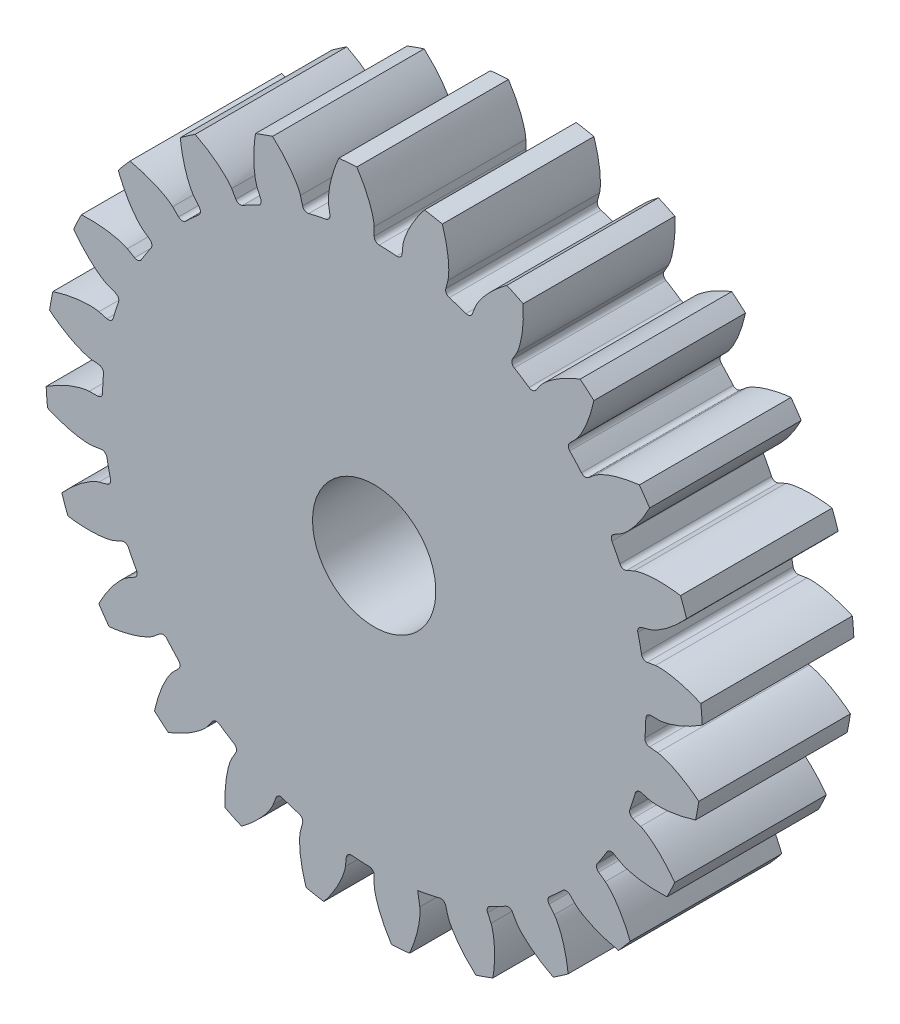
SolidWorks part; units mm, degrees
material "Brass"
ref_plane "Front Plane" through (0, 0, 0) normal (0, 0, 1) x (1, 0, 0)
ref_plane "Top Plane" through (0, 0, 0) normal (0, 1, 0) x (1, 0, 0)
ref_plane "Right Plane" through (0, 0, 0) normal (1, 0, 0) x (0, 0, -1)
sketch "Sketch3" plane through (0, 0, 0) normal (0, 0, 1) x (1, 0, 0)
  circle A0 centre (0, 0) radius 6.5
  dimension "D1" = 13
extrude "Boss-Extrude1" add sketch "Sketch3" along normal blind 3 contours A0
sketch "Sketch4" plane through (0, 0, 0) normal (0, 0, 1) x (1, 0, 0)
  line L0 (5.375, 0) -> (5.6382, 0)
  line L1 (0, 0) -> (6.4917, -0.3284) construction
  line L2 (5.3476, -0.5424) -> (5.6094, -0.569)
  circle A0 centre (0, 0) radius 6 construction
  circle A1 centre (0, 0) radius 5.6382 construction
  arc A2 (5.3476, -0.5424) -> (5.375, 0) centre (0, 0) ccw
  circle A3 centre (0, 0) radius 6.5 construction
  spline S0 degree 4 poles (5.6382, 0) (5.6436, 0.0001) (5.6538, 0.0007) (5.6704, 0.0021) (5.7032, 0.0063) (5.7401, 0.0126) (5.7816, 0.0215) (5.8259, 0.0327) (5.8637, 0.0433) (5.9012, 0.0548) (5.9385, 0.0672) (5.9834, 0.0831) (6.0369, 0.1037) (6.099, 0.1298) (6.1689, 0.1617) (6.2395, 0.1968) (6.3084, 0.2334) (6.3772, 0.2727) (6.4433, 0.3125) (6.5112, 0.3562) (6.5735, 0.3977) (6.6423, 0.4468) (6.6975, 0.4873) (6.7693, 0.5433) (6.8114, 0.5772) (6.8602, 0.6179) (6.8817, 0.6364) (6.895, 0.6478) knots 0 0 0 0 0 0.015084 0.028532 0.04661 0.092111 0.119476 0.146842 0.174209 0.201575 0.228941 0.256307 0.307035 0.361767 0.4165 0.471232 0.525964 0.580697 0.635429 0.690161 0.744894 0.799626 0.854358 0.909091 0.954545 1 1 1 1 1 construction
  spline S1 degree 4 poles (5.6382, 0) (5.6436, 0.0001) (5.6538, 0.0007) (5.6704, 0.0021) (5.7032, 0.0063) (5.7401, 0.0126) (5.7816, 0.0215) (5.8259, 0.0327) (5.8637, 0.0433) (5.9012, 0.0548) (5.9385, 0.0672) (5.9834, 0.0831) (6.0369, 0.1037) (6.099, 0.1298) (6.1689, 0.1617) (6.2395, 0.1968) (6.3084, 0.2334) (6.3772, 0.2727) (6.4433, 0.3125) (6.5112, 0.3562) (6.5735, 0.3977) (6.6423, 0.4468) (6.6975, 0.4873) (6.7537, 0.5312) (6.781, 0.5528) (6.7948, 0.5641) knots 0 0 0 0 0 0.015084 0.028532 0.04661 0.092111 0.119476 0.146842 0.174209 0.201575 0.228941 0.256307 0.307035 0.361767 0.4165 0.471232 0.525964 0.580697 0.635429 0.690161 0.744894 0.799626 0.854358 0.909091 0.909091 0.909091 0.909091 0.909091
  spline S2 degree 4 poles (106.284, -15.4902) (106.3203, -15.496) (106.4217, -15.5139) (106.6124, -15.5542) (106.9218, -15.6289) (107.4928, -15.787) (108.3484, -16.0665) (109.2774, -16.4238) (110.2481, -16.846) (111.0925, -17.2464) (111.7606, -17.5817) (112.5627, -18.0056) (113.5166, -18.5412) (114.6147, -19.2012) (115.8472, -19.9983) (117.0769, -20.8493) (118.2809, -21.7356) (119.4604, -22.6553) (120.4702, -23.4858) (121.322, -24.2171) (122.1596, -24.9594) (122.8519, -25.5935) (123.5262, -26.2293) (124.2037, -26.8891) (124.7206, -27.4019) (125.2693, -27.9609) (125.7445, -28.4521) (126.1894, -28.925) (126.4234, -29.1763) (126.5387, -29.301) knots 0 0 0 0 0 0.005377 0.015084 0.028532 0.04661 0.092111 0.146842 0.174209 0.201575 0.228941 0.256307 0.307035 0.361767 0.4165 0.471232 0.525964 0.580697 0.635429 0.662795 0.690161 0.744894 0.77226 0.799626 0.826992 0.854358 0.881725 0.909091 0.909091 0.909091 0.909091 0.909091
  spline S3 degree 4 poles (5.6094, -0.569) (5.6147, -0.5696) (5.6248, -0.5712) (5.6413, -0.5744) (5.6734, -0.5818) (5.7095, -0.5919) (5.7499, -0.6049) (5.7929, -0.6205) (5.8294, -0.6348) (5.8656, -0.6501) (5.9014, -0.6661) (5.9444, -0.6866) (5.9956, -0.7124) (6.0548, -0.7446) (6.1211, -0.7834) (6.1878, -0.8255) (6.2526, -0.8688) (6.3171, -0.9149) (6.3789, -0.9612) (6.442, -1.0115) (6.4998, -1.0591) (6.5632, -1.1149) (6.6141, -1.1607) (6.6656, -1.21) (6.6906, -1.2344) (6.7032, -1.2469) knots 0 0 0 0 0 0.015084 0.028532 0.04661 0.092111 0.119476 0.146842 0.174209 0.201575 0.228941 0.256307 0.307035 0.361767 0.4165 0.471232 0.525964 0.580697 0.635429 0.690161 0.744894 0.799626 0.854358 0.909091 0.909091 0.909091 0.909091 0.909091
  dimension "D1" = 12
  dimension "D2" = 11.2763
  dimension "D3" = 10.75
  dimension "D4" = 2.896
sketch "Sketch5" plane through (0, 0, 0) normal (0, 0, -1) x (-1, 0, 0)
sketch "Sketch6" plane through (0, 0, 3) normal (0, 0, 1) x (1, 0, 0)
  spline S0 degree 4 poles (5.584, -0.5665) (5.585, -0.5665) (5.5873, -0.5664) (5.5951, -0.5671) (5.607, -0.5685) (5.6218, -0.571) (5.6516, -0.5769) (5.6822, -0.5849) (5.7252, -0.5972) (5.7693, -0.6124) (5.8191, -0.6312) (5.8672, -0.6515) (5.9207, -0.6758) (5.9849, -0.7075) (6.0596, -0.7478) (6.144, -0.7981) (6.2321, -0.8553) (6.3184, -0.9165) (6.4018, -0.9797) (6.4843, -1.0471) (6.5626, -1.1145) (6.6423, -1.1885) (6.7141, -1.2577) (6.7935, -1.3404) (6.8551, -1.406) (6.9366, -1.4999) (6.9806, -1.5525) (7.0336, -1.6182) (7.0565, -1.6477) (7.07, -1.6651) knots 0 0 0 0 0 0.002436 0.00621 0.013651 0.025362 0.041878 0.0605 0.087814 0.115747 0.143681 0.171614 0.199547 0.239932 0.295799 0.351666 0.407532 0.463399 0.519266 0.575132 0.630999 0.686865 0.742732 0.798599 0.854465 0.910332 0.955166 1 1 1 1 1 construction
  spline S1 degree 4 poles (5.6094, -0.569) (5.6143, -0.5697) (5.6258, -0.5718) (5.6516, -0.5769) (5.6822, -0.5849) (5.7252, -0.5972) (5.7693, -0.6124) (5.8191, -0.6312) (5.8672, -0.6515) (5.9207, -0.6758) (5.9849, -0.7075) (6.0596, -0.7478) (6.144, -0.7981) (6.2321, -0.8553) (6.3184, -0.9165) (6.4018, -0.9797) (6.4843, -1.0471) (6.5626, -1.1145) (6.6423, -1.1885) (6.7141, -1.2577) (6.7935, -1.3404) (6.8551, -1.406) (6.9194, -1.4801) (6.9491, -1.5151) (6.9642, -1.5332) knots 0.013651 0.013651 0.013651 0.013651 0.013651 0.025362 0.041878 0.0605 0.087814 0.115747 0.143681 0.171614 0.199547 0.239932 0.295799 0.351666 0.407532 0.463399 0.519266 0.575132 0.630999 0.686865 0.742732 0.798599 0.854465 0.910332 0.910332 0.910332 0.910332 0.910332
sketch "Sketch7" plane through (0, 0, 0) normal (0, 0, -1) x (-1, 0, 0)
extrude "Cut-Extrude1" cut sketch "Sketch4" against normal through all and the other way through all contours S3 L2 A2 L0 S1
pattern_circular "CirPattern1" count 24 over 360 about axis through (0, 0, 0) along (0, 0, 1) of "Cut-Extrude1"
fillet "Fillet1" radius 0.1 48 edges at (5.3057, 0.8601, 1.5) (5.1919, 1.3912, 1.5) (4.9023, 2.204, 1.5) (4.6549, 2.6875, 1.5) (4.1649, 3.3977, 1.5) (3.8007, 3.8007, 1.5) (3.1435, 4.3599, 1.5) (2.6875, 4.6549, 1.5) (1.908, 5.025, 1.5) (1.3912, 5.1919, 1.5) (0.5424, 5.3476, 1.5) (0, 5.375, 1.5) (-0.8601, 5.3057, 1.5) (-1.3912, 5.1919, 1.5) (-2.204, 4.9023, 1.5) (-2.6875, 4.6549, 1.5) (-3.3977, 4.1649, 1.5) (-3.8007, 3.8007, 1.5) (-4.3599, 3.1435, 1.5) (-4.6549, 2.6875, 1.5) (-5.025, 1.908, 1.5) (-5.1919, 1.3912, 1.5) (-5.3476, 0.5424, 1.5) (-5.375, 0, 1.5) (-5.3057, -0.8601, 1.5) (-5.1919, -1.3912, 1.5) (-4.9023, -2.204, 1.5) (-4.6549, -2.6875, 1.5) (-4.1649, -3.3977, 1.5) (-3.8007, -3.8007, 1.5) (-3.1435, -4.3599, 1.5) (-2.6875, -4.6549, 1.5) (-1.908, -5.025, 1.5) (-1.3912, -5.1919, 1.5) (-0.5424, -5.3476, 1.5) (0, -5.375, 1.5) (0.9022, -5.5655, 1.5) (1.3912, -5.1919, 1.5) (2.6875, -4.6549, 1.5) (2.204, -4.9023, 1.5) (3.3977, -4.1649, 1.5) (3.8007, -3.8007, 1.5) (4.3599, -3.1435, 1.5) (4.6549, -2.6875, 1.5) (5.1919, -1.3912, 1.5) (5.025, -1.908, 1.5) (5.3476, -0.5424, 1.5) (5.375, 0, 1.5)
sketch "Sketch8" plane through (0, 0, 0) normal (0, 0, -1) x (-1, 0, 0)
  circle A0 centre (0, 0) radius 1.22
extrude "Cut-Extrude2" cut sketch "Sketch8" against normal through all
sketch "Sketch9" plane through (0, 0, 0) normal (0, 0, -1) x (-1, 0, 0)
  circle A0 centre (0, 0) radius 6
equation "\"P\"= 2'Diametral Pitch"
equation "\"N\"= 24'Numver of teeth"
equation "\"phi\"= 20deg'Pressure Angle"
equation "\"a\"= 1 / \"P\"'Addendum"
equation "\"b\"= 1.25 / \"P\"'Dedendun"
equation "\"c\"= \"b\" - \"a\"'clearance"
equation "\"dp\"= \"N\" / \"P\"'pitch circle diameter"
equation "\"db\"= \"dp\" * cos ( \"phi\" )'base circle diameter"
equation "\"D1@Sketch3\"= \"dp\" + 2 * \"a\""
equation "\"D1@Sketch4\"= \"dp\"'Pitch circle diametr"
equation "\"D2@Sketch4\"= \"db\"'Base Circle"
equation "\"D3@Sketch4\"= \"dp\" - 2 * \"b\""
equation "\"alpha\"= sqr ( \"dp\" ^ 2 - \"db\" ^ 2 ) / \"db\" * 180 / pi - \"phi\""
equation "\"Beta\"= ( 360 / ( 4 * \"N\" ) - \"alpha\" ) * 2"
equation "\"D4@Sketch4\"= 360 / ( 4 * \"N\" ) - \"alpha\""
